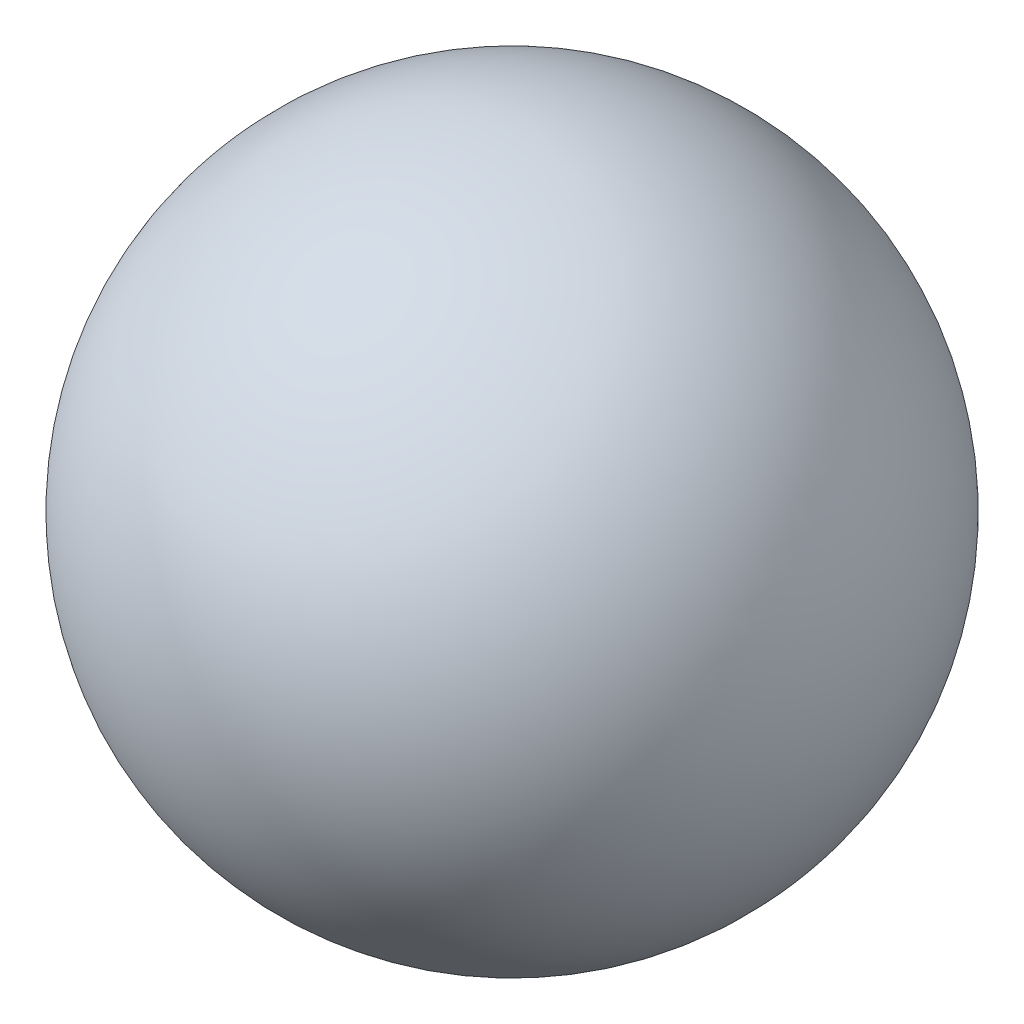
SolidWorks part; units mm, degrees
ref_plane "Front Plane" through (0, 0, 0) normal (0, 0, 1) x (1, 0, 0)
ref_plane "Top Plane" through (0, 0, 0) normal (0, 1, 0) x (1, 0, 0)
ref_plane "Right Plane" through (0, 0, 0) normal (1, 0, 0) x (0, 0, -1)
sketch "Sketch1" plane through (0, 0, 0) normal (0, 0, 1) x (1, 0, 0)
  line L0 (2.7799, -1.605) -> (4.0941, -2.3638)
  line L1 (3.1085, -1.7947) -> (3.6776, -2.1232) construction
  arc A0 (4.0941, -2.3638) -> (2.7799, -1.605) centre (3.437, -1.9844) ccw
revolve "Revolve1" add sketch "Sketch1" angle 360 about L1
